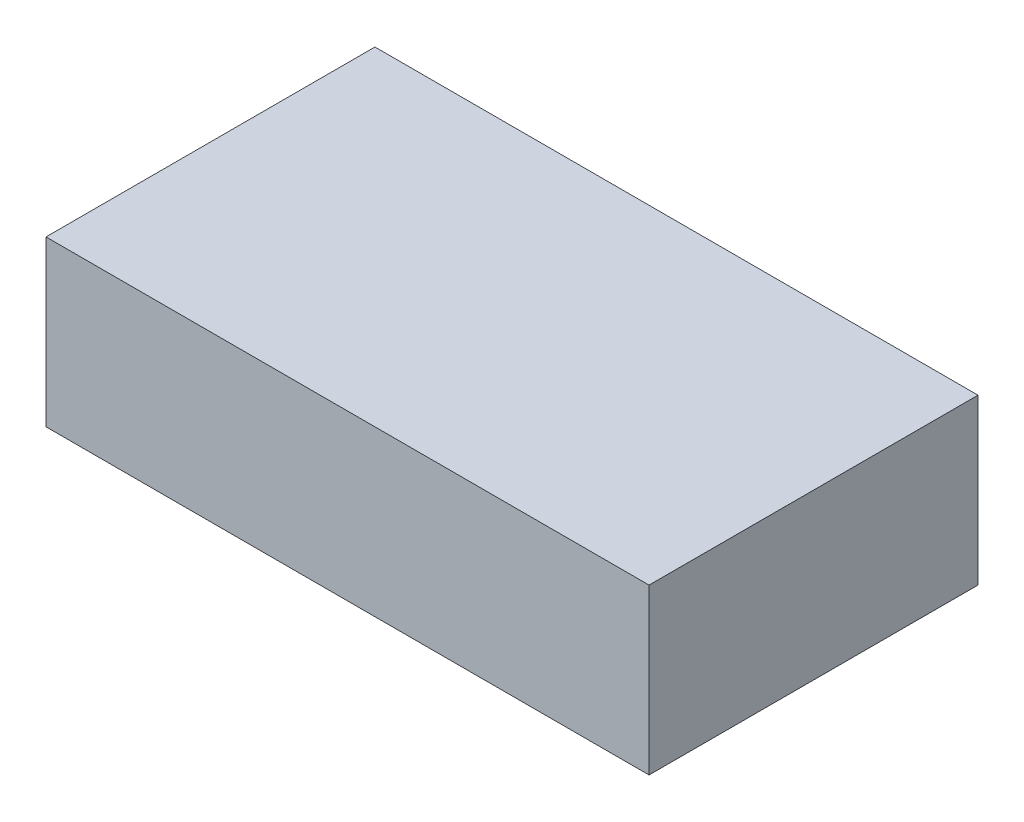
SolidWorks part; units mm, degrees
material "Acrilico TEC"
ref_plane "Front Plane" through (0, 0, 0) normal (0, 0, 1) x (1, 0, 0)
ref_plane "Top Plane" through (0, 0, 0) normal (0, 1, 0) x (1, 0, 0)
ref_plane "Right Plane" through (0, 0, 0) normal (1, 0, 0) x (0, 0, -1)
sketch "Sketch1" plane through (0, 0, 0) normal (0, 1, 0) x (1, 0, 0)
  line L1 (0, 0) -> (22, 0)
  line L2 (0, 0) -> (0, 12)
  line L3 (0, 12) -> (22, 12)
  line L4 (22, 0) -> (22, 12)
  dimension "D1" = 22
  dimension "D2" = 12
extrude "Boss-Extrude1" add sketch "Sketch1" along normal blind 6
